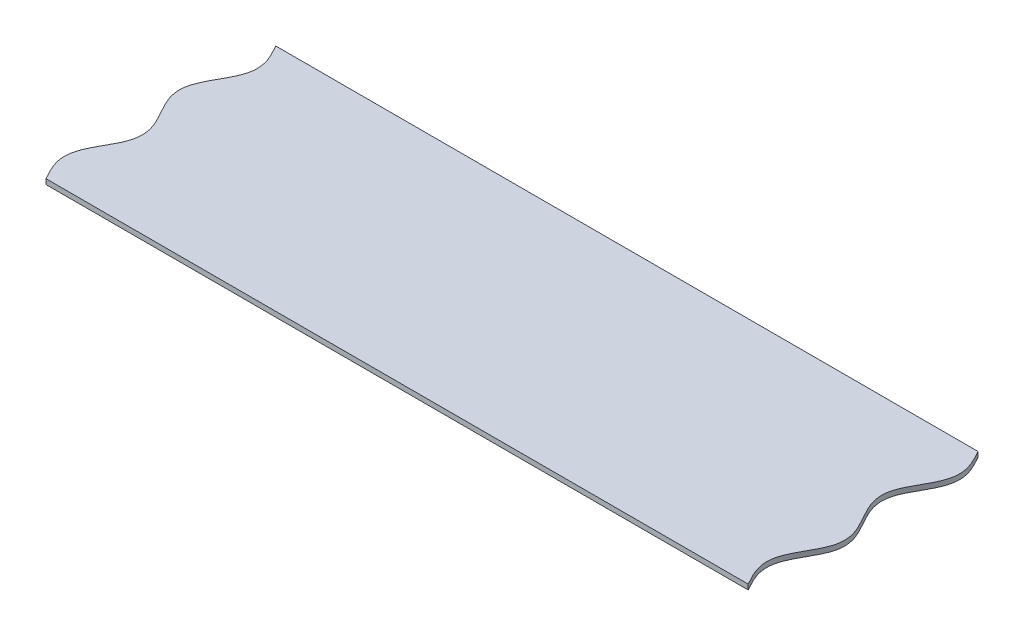
SolidWorks part; units mm, degrees
ref_plane "Front Plane" through (0, 0, 0) normal (0, 0, 1) x (1, 0, 0)
ref_plane "Top Plane" through (0, 0, 0) normal (0, 1, 0) x (1, 0, 0)
ref_plane "Right Plane" through (0, 0, 0) normal (1, 0, 0) x (0, 0, -1)
sketch "Sketch1" plane through (0, 0, 0) normal (0, 1, 0) x (1, 0, 0)
  line L0 (0, 0) -> (55, 0)
  line L2 (55, -18) -> (0, -18)
  spline S0 degree 4 poles (-0.7546, 1.764) (-0.7382, 1.6791) (-0.7035, 1.5186) (-0.6248, 1.2703) (-0.513, 0.984) (-0.3625, 0.6698) (-0.2435, 0.4384) (-0.0455, 0.0806) (0.0491, -0.0871) (0.292, -0.5262) (0.4452, -0.8327) (0.6239, -1.2441) (0.7596, -1.7212) (0.8329, -2.2515) (0.7507, -2.9656) (0.4437, -3.7158) (0.0505, -4.4103) (-0.3487, -5.1224) (-0.6487, -5.7703) (-0.8267, -6.469) (-0.7986, -7.251) (-0.4953, -8.1423) (-0.0001, -9) (0.4954, -9.8578) (0.7997, -10.7484) (0.8291, -11.5306) (0.6518, -12.2291) (0.3893, -12.7986) (0.1313, -13.2714) (-0.1076, -13.6968) (-0.3248, -14.0918) (-0.5595, -14.5778) (-0.7653, -15.1703) (-0.8284, -15.7519) (-0.7622, -16.272) (-0.6389, -16.6907) (-0.5232, -16.9916) (-0.3709, -17.3133) (-0.251, -17.5478) (-0.0473, -17.9161) (0.0443, -18.0785) (0.2449, -18.4408) (0.3617, -18.6679) (0.5143, -18.9857) (0.6101, -19.2316) (0.6918, -19.4776) (0.73, -19.6379) (0.7478, -19.7219) (0.7561, -19.7644) knots 0 0 0 0 0 0.014648 0.029297 0.042756 0.056215 0.069674 0.083133 0.096936 0.110738 0.138342 0.153421 0.1685 0.198657 0.228814 0.276483 0.306641 0.336798 0.369389 0.399546 0.429703 0.469833 0.530148 0.570278 0.600435 0.630592 0.663183 0.693341 0.708419 0.723498 0.747333 0.771168 0.801325 0.831482 0.84656 0.861639 0.875441 0.889243 0.903046 0.916848 0.93031 0.943772 0.957234 0.970697 0.985348 0.992674 1 1 1 1 1 construction
  spline S1 degree 4 poles (0, 0) (0.0325, -0.0582) (0.0967, -0.1732) (0.292, -0.5262) (0.4452, -0.8327) (0.6239, -1.2441) (0.7596, -1.7212) (0.8329, -2.2515) (0.7507, -2.9656) (0.4437, -3.7158) (0.0505, -4.4103) (-0.3487, -5.1224) (-0.6487, -5.7703) (-0.8267, -6.469) (-0.7986, -7.251) (-0.4953, -8.1423) (-0.0001, -9) (0.4954, -9.8578) (0.7997, -10.7484) (0.8291, -11.5306) (0.6518, -12.2291) (0.3893, -12.7986) (0.1313, -13.2714) (-0.1076, -13.6968) (-0.3248, -14.0918) (-0.5595, -14.5778) (-0.7653, -15.1703) (-0.8284, -15.7519) (-0.7622, -16.272) (-0.6389, -16.6907) (-0.5232, -16.9916) (-0.3709, -17.3133) (-0.251, -17.5478) (-0.0973, -17.8258) (-0.0325, -17.9418) (0, -18) knots 0.083133 0.083133 0.083133 0.083133 0.083133 0.096936 0.110738 0.138342 0.153421 0.1685 0.198657 0.228814 0.276483 0.306641 0.336798 0.369389 0.399546 0.429703 0.469833 0.530148 0.570278 0.600435 0.630592 0.663183 0.693341 0.708419 0.723498 0.747333 0.771168 0.801325 0.831482 0.84656 0.861639 0.875441 0.889243 0.903046 0.916848 0.916848 0.916848 0.916848 0.916848
  spline S2 degree 4 poles (54.2455, 1.7638) (54.2613, 1.68) (54.2976, 1.5166) (54.3734, 1.2735) (54.4893, 0.98) (54.6341, 0.6758) (54.761, 0.4304) (55.0002, -0.0021) (55.0755, -0.1332) (55.2841, -0.5136) (55.3599, -0.668) (55.393, -0.7358) (55.4373, -0.828) (55.4899, -0.9417) (55.5457, -1.0721) (55.6065, -1.228) (55.6621, -1.3901) (55.7106, -1.5581) (55.7598, -1.771) (55.7979, -2.031) (55.8122, -2.425) (55.7179, -3.0491) (55.4431, -3.7143) (55.0508, -4.4111) (54.6511, -5.122) (54.3514, -5.7706) (54.1732, -6.4689) (54.2014, -7.2511) (54.5047, -8.1422) (54.9999, -9) (55.4954, -9.8577) (55.7997, -10.7484) (55.8291, -11.5306) (55.6518, -12.2291) (55.3893, -12.7986) (55.1313, -13.2714) (54.8924, -13.6968) (54.6752, -14.0919) (54.4404, -14.5777) (54.2347, -15.1704) (54.1715, -15.7519) (54.2378, -16.2721) (54.361, -16.6906) (54.477, -16.9919) (54.6288, -17.3128) (54.7492, -17.5482) (54.9526, -17.916) (55.0443, -18.0786) (55.245, -18.441) (55.3611, -18.6669) (55.4953, -18.9458) (55.5799, -19.1551) (55.6662, -19.3952) (55.7112, -19.5551) (55.74, -19.6804) (55.756, -19.7642) knots 0 0 0 0 0 0.014648 0.029297 0.042756 0.056215 0.069674 0.083133 0.110738 0.114188 0.117639 0.121089 0.12454 0.131441 0.138342 0.145882 0.153421 0.16096 0.1685 0.183578 0.198657 0.228814 0.276483 0.306641 0.336798 0.369389 0.399546 0.429703 0.469833 0.530148 0.570278 0.600435 0.630592 0.663183 0.693341 0.708419 0.723498 0.747333 0.771168 0.801325 0.831482 0.84656 0.861639 0.875441 0.889243 0.903046 0.916848 0.93031 0.943772 0.957234 0.970697 0.978022 0.985348 1 1 1 1 1 construction
  spline S3 degree 4 poles (55, 0) (55.065, -0.1165) (55.134, -0.2399) (55.2841, -0.5136) (55.3599, -0.668) (55.393, -0.7358) (55.4373, -0.828) (55.4899, -0.9417) (55.5457, -1.0721) (55.6065, -1.228) (55.6621, -1.3901) (55.7106, -1.5581) (55.7598, -1.771) (55.7979, -2.031) (55.8122, -2.425) (55.7179, -3.0491) (55.4431, -3.7143) (55.0508, -4.4111) (54.6511, -5.122) (54.3514, -5.7706) (54.1732, -6.4689) (54.2014, -7.2511) (54.5047, -8.1422) (54.9999, -9) (55.4954, -9.8577) (55.7997, -10.7484) (55.8291, -11.5306) (55.6518, -12.2291) (55.3893, -12.7986) (55.1313, -13.2714) (54.8924, -13.6968) (54.6752, -14.0919) (54.4404, -14.5777) (54.2347, -15.1704) (54.1715, -15.7519) (54.2378, -16.2721) (54.361, -16.6906) (54.477, -16.9919) (54.6288, -17.3128) (54.7492, -17.5482) (54.9027, -17.8258) (54.9675, -17.9418) (55, -18) knots 0.083133 0.083133 0.083133 0.083133 0.083133 0.110738 0.114188 0.117639 0.121089 0.12454 0.131441 0.138342 0.145882 0.153421 0.16096 0.1685 0.183578 0.198657 0.228814 0.276483 0.306641 0.336798 0.369389 0.399546 0.429703 0.469833 0.530148 0.570278 0.600435 0.630592 0.663183 0.693341 0.708419 0.723498 0.747333 0.771168 0.801325 0.831482 0.84656 0.861639 0.875441 0.889243 0.903046 0.916848 0.916848 0.916848 0.916848 0.916848
  point P3 (55, -0.3308)
  point P4 (55, -18.3322)
  point P5 (55.0896, -18)
  dimension "D4" = 18
  dimension "D5" = 55
extrude "Boss-Extrude1" add sketch "Sketch1" along normal blind 0.4
